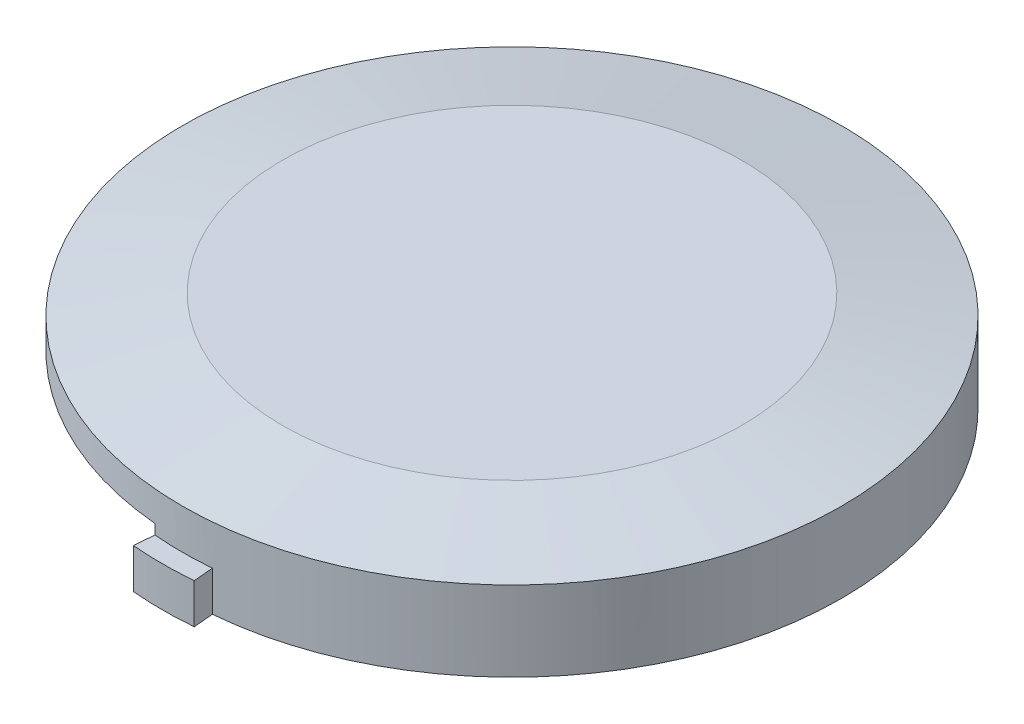
SolidWorks part; units mm, degrees
material "BUTYL"
ref_plane "Front Plane" through (0, 0, 0) normal (0, 0, 1) x (1, 0, 0)
ref_plane "Top Plane" through (0, 0, 0) normal (0, 1, 0) x (1, 0, 0)
ref_plane "Right Plane" through (0, 0, 0) normal (1, 0, 0) x (0, 0, -1)
sketch "Sketch1" plane through (0, 0, 0) normal (0, 1, 0) x (1, 0, 0)
  circle A0 centre (0, 0) radius 16.5
extrude "Boss-Extrude1" add sketch "Sketch1" along normal blind 5 contours A0
chamfer "Chamfer2" distance 1 distance2 5 1 edges at (0, 5, 16.5)
sketch "Sketch3" plane through (0, 0, 0) normal (0, 1, 0) x (1, 0, 0)
  circle A0 centre (0, 0) radius 13.5
extrude "Cut-Extrude1" cut sketch "Sketch3" along normal blind 2.8
sketch "Sketch10" plane through (0, 0, 0) normal (1, 0, 0) x (0, 0, -1)
  line L0 (0, 0) -> (0, 2.3355)
  line L1 (-16.5, 0) -> (16.5, 0) construction
sketch "Sketch5" plane through (0, 0, 0) normal (1, 0, 0) x (0, 0, -1)
  line L5 (16.5, 0) -> (17.5, 0)
  line L6 (16.5, 0) -> (16.5, 2)
  line L7 (16.5, 2) -> (17.5, 2)
  line L8 (17.5, 0) -> (17.5, 2)
sketch "Sketch6" plane through (0, 0, 0) normal (1, 0, 0) x (0, 0, -1)
  line L5 (-16.5, 0) -> (-17.5, 0)
  line L6 (-16.5, 0) -> (-16.5, 2)
  line L7 (-16.5, 2) -> (-17.5, 2)
  line L8 (-17.5, 0) -> (-17.5, 2)
revolve "Revolve4" add sketch "Sketch5" angle 5 about L0 other way angle 5
revolve "Revolve6" add sketch "Sketch6" angle 5 about L0 other way angle 5
sketch "Sketch9" plane through (0, 0, 0) normal (0, 0, 1) x (1, 0, 0)
  line L5 (-16.5, 4) -> (-16.5, 0) construction
  line L6 (0, 0) -> (-16.5, 0)
  line L7 (0, 0) -> (0, 2.5)
  line L8 (0, 2.5) -> (-16.5, 2.5)
  line L9 (-16.5, 0) -> (-16.5, 2.5)
revolve "Cut-Revolve1" cut sketch "Sketch9" angle 85 about L7 other way angle 10
